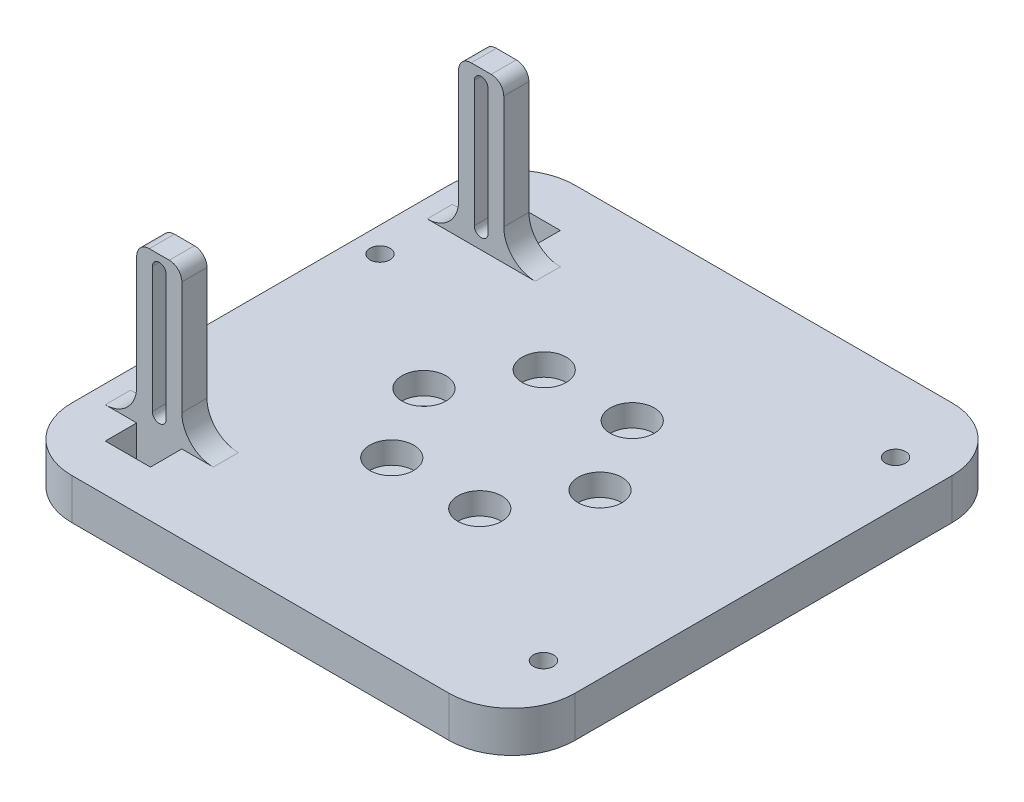
SolidWorks part; units mm, degrees
material "ABS"
ref_plane "Front Plane" through (0, 0, 0) normal (0, 0, 1) x (1, 0, 0)
ref_plane "Top Plane" through (0, 0, 0) normal (0, 1, 0) x (1, 0, 0)
ref_plane "Right Plane" through (0, 0, 0) normal (1, 0, 0) x (0, 0, -1)
sketch "草图1" plane through (0, 0, 0) normal (0, 1, 0) x (1, 0, 0)
  line L1 (-40, 40) -> (40, 40)
  line L2 (-40, 40) -> (-40, -40)
  line L3 (-40, -40) -> (40, -40)
  line L4 (40, 40) -> (40, -40)
  line L5 (-40, 40) -> (40, -40) construction
  line L6 (-40, -40) -> (40, 40) construction
  point P0 (0, 0)
  dimension "D1" = 80
  dimension "D2" = 80
extrude "凸台-拉伸1" add sketch "草图1" along normal blind 6.5
fillet "圆角1" radius 10 4 edges at (-40, 3.25, -40) (40, 3.25, -40) (-40, 3.25, 40) (40, 3.25, 40)
ref_plane "基准面1" through (0, 0, 0) normal (-1, 0, 0) x (0, 0, 1)
sketch "草图55" plane through (0, 6.5, 0) normal (0, 1, 0) x (1, 0, 0)
  circle A0 centre (0, 0) radius 14 construction
  circle A1 centre (-7, -12.1244) radius 1.5
  circle A2 centre (-14, 0) radius 1.5
  circle A3 centre (-7, 12.1244) radius 1.5
  circle A4 centre (7, 12.1244) radius 1.5
  circle A5 centre (7, -12.1244) radius 1.5
  circle A6 centre (14, 0) radius 1.5
extrude "切除-拉伸33" cut sketch "草图55" against normal blind 10
sketch "草图57" plane through (0, 6.5, 0) normal (0, 1, 0) x (1, 0, 0)
  circle A0 centre (14, 0) radius 3.5
  circle A1 centre (7, -12.1244) radius 3.5
  circle A2 centre (-7, -12.1244) radius 3.5
  circle A3 centre (-14, 0) radius 3.5
  circle A4 centre (-7, 12.1244) radius 3.5
  circle A5 centre (7, 12.1244) radius 3.5
  point P15 (0, 0)
  dimension "D1" = 7
  dimension "D2" = 6
extrude "切除-拉伸34" cut sketch "草图57" against normal blind 3.5
sketch "草图58" plane through (0, 6.5, 0) normal (0, 1, 0) x (1, 0, 0)
  line L0 (0, 0) -> (-23.314, 0) construction
  line L7 (-32.091, 32.6) -> (-24.911, 27.6) construction
  line L8 (-32.091, -27.6) -> (-24.911, -27.6)
  line L17 (-32.091, -27.6) -> (-32.091, -32.6)
  line L18 (-32.091, -32.6) -> (-24.911, -32.6)
  line L19 (-24.911, -27.6) -> (-24.911, -32.6)
  line L20 (-32.091, -27.6) -> (-24.911, -32.6) construction
  line L21 (-32.091, -32.6) -> (-24.911, -27.6) construction
  line L22 (-32.091, 27.6) -> (-24.911, 32.6) construction
  line L24 (-24.911, 27.6) -> (-24.911, 32.6)
  line L25 (-32.091, 32.6) -> (-24.911, 32.6)
  line L26 (-32.091, 27.6) -> (-32.091, 32.6)
  line L27 (-32.091, 27.6) -> (-24.911, 27.6)
  dimension "D1" = 7.18
extrude "切除-拉伸35" cut sketch "草图58" against normal blind 7.5
sketch "草图60" plane through (0, 6.5, 0) normal (0, 1, 0) x (1, 0, 0)
  line L0 (0, 0) -> (-40, 0) construction
  line L1 (-40, 30) -> (-40, -30) construction
  line L2 (0, 0) -> (0, -49.7364) construction
  circle A0 centre (-36, -15) radius 1.6
  circle A1 centre (-36, 15) radius 1.6
  circle A2 centre (33, -28) radius 1.6
  circle A3 centre (33, 28) radius 1.6
  dimension "D1" = 3.2
  dimension "D4" = 3.2
  dimension "D2" = 15
  dimension "D3" = 36
  dimension "D5" = 33
  dimension "D6" = 28
extrude "切除-拉伸36" cut sketch "草图60" against normal blind 10
sketch "草图61" plane through (0, 0, 0) normal (0, -1, 0) x (1, 0, 0)
  circle A0 centre (-36, 15) radius 3.15
  circle A1 centre (-36, -15) radius 3.15
  circle A2 centre (33, -28) radius 3.15
  circle A3 centre (33, 28) radius 3.15
  dimension "D1" = 6.3
extrude "切除-拉伸37" cut sketch "草图61" against normal blind 3
sketch "草图62" plane through (0, 6.5, 0) normal (0, 1, 0) x (1, 0, 0)
  line L1 (-32.091, 27.6) -> (-24.911, 27.6)
  line L2 (-32.091, 27.6) -> (-32.091, 23.6)
  line L3 (-32.091, 23.6) -> (-24.911, 23.6)
  line L4 (-24.911, 27.6) -> (-24.911, 23.6)
  dimension "D1" = 4
extrude "凸台-拉伸8" add sketch "草图62" along normal blind 25
fillet "圆角8" radius 5 2 edges at (-24.911, 6.5, -25.6) (-32.091, 6.5, -25.6)
sketch "草图63" plane through (0, 0, -27.6) normal (0, 0, -1) x (-1, 0, 0)
  line L0 (28.501, 29.3134) -> (28.501, 9.3134) construction
  line L1 (29.601, 29.3134) -> (29.601, 9.3134)
  line L2 (27.401, 29.3134) -> (27.401, 9.3134)
  line L3 (28.501, 31.5) -> (28.501, 33.8275) construction
  line L4 (24.911, 31.5) -> (32.091, 31.5) construction
  arc A0 (29.601, 29.3134) -> (27.401, 29.3134) centre (28.501, 29.3134) ccw
  arc A1 (27.401, 9.3134) -> (29.601, 9.3134) centre (28.501, 9.3134) ccw
  point P2 (28.501, 19.3134)
  dimension "D1" = 1.1
  dimension "D2" = 20
extrude "切除-拉伸38" cut sketch "草图63" against normal blind 25
fillet "圆角9" radius 2 2 edges at (-32.091, 31.5, -25.6) (-24.911, 31.5, -25.6)
mirror "镜向1" about plane through (0, 0, 0) normal (0, 0, 1) of "凸台-拉伸8", "圆角8", "切除-拉伸38", "圆角9"
